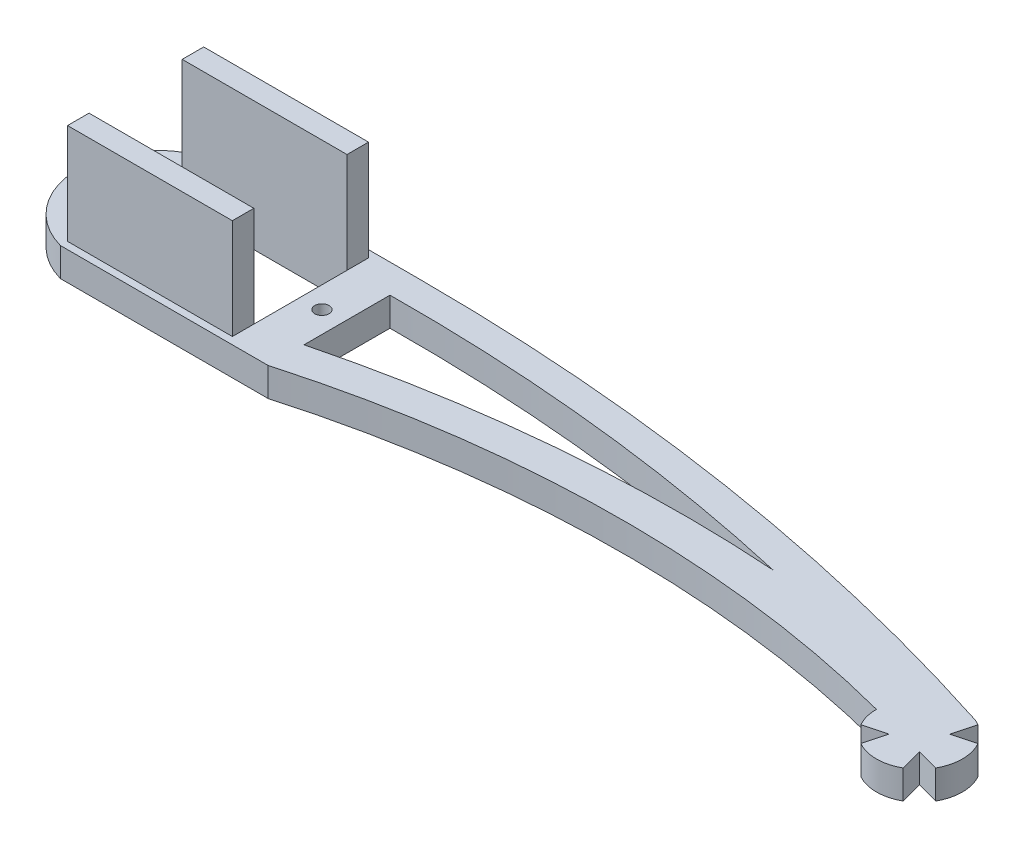
SolidWorks part; units mm, degrees
ref_plane "前视基准面" through (0, 0, 0) normal (0, 0, 1) x (1, 0, 0)
ref_plane "上视基准面" through (0, 0, 0) normal (0, 1, 0) x (1, 0, 0)
ref_plane "右视基准面" through (0, 0, 0) normal (1, 0, 0) x (0, 0, -1)
sketch "草图1" plane through (0, 0, 0) normal (0, 1, 0) x (1, 0, 0)
  line L0 (17.5, -10.5) -> (-11.5, -10.5)
  line L1 (-11.5, -6.5) -> (11.5, -6.5)
  line L2 (-11.5, -6.5) -> (-11.5, 6.5)
  line L3 (-11.5, 6.5) -> (11.5, 6.5)
  line L4 (11.5, -6.5) -> (11.5, 6.5)
  line L5 (-11.5, -6.5) -> (11.5, 6.5) construction
  line L6 (-11.5, 6.5) -> (11.5, -6.5) construction
  line L7 (-11.5, 3) -> (-12.5, 3)
  line L9 (-11.5, -3) -> (-12.5, -3)
  line L10 (-12.5, 3) -> (-12.5, -3)
  line L11 (0, 0) -> (50000, 0) construction
  line L12 (17.5, 10.5) -> (-11.5, 10.5)
  line L13 (17.5, -10.5) -> (17.5, 10.5)
  arc A1 (-11.5, -10.5) -> (-11.5, 10.5) centre (-8.6094, 0) cw
  point P0 (0, 0)
  point P14 (-12.5, 0)
  point P20 (-19.5, 0)
  dimension "D5" = 4
  dimension "D6" = 8
  dimension "D1" = 23
  dimension "D2" = 13
  dimension "D3" = 1
  dimension "D4" = 6
  dimension "D7" = 6
extrude "凸台-拉伸1" add sketch "草图1" along normal mid plane 4 contours A1 L0 L13 L12 L10 L7 L2 L3 L4 L1 L9
sketch "草图2" plane through (0, 2, 0) normal (0, 1, 0) x (1, 0, 0)
  line L0 (17.5, 10.5) -> (-11.5, 10.5) construction
  line L1 (11.5, -6.5) -> (11.5, 6.5) construction
  line L2 (107.5, -9.6143) -> (98.1207, -9.6143) construction
  line L3 (17.5, -10.5) -> (17.5, 10.5)
  line L4 (17.5, -5.5) -> (17.5, 6.5)
  line L5 (-11.5, -6.5) -> (11.5, -6.5) construction
  line L7 (-11.5, 6.5) -> (11.5, 6.5) construction
  arc A0 (17.5, -10.5) -> (101.5, -9.6143) centre (61.1278, -164.4371) cw
  arc A1 (17.5, 10.5) -> (109.3367, -3.9024) centre (17.5, -289.5) cw
  circle A2 centre (107.5, -9.6143) radius 6
  arc A3 (17.5, 6.5) -> (77.5, 0) centre (19.6864, -253.4908) cw
  arc A4 (17.5, -5.5) -> (77.5, 0) centre (64.6245, -189.5632) cw
  point P16 (64.5211, -2.4548)
  point P21 (0, 0)
  point P22 (63.9796, 0)
  point P23 (62.1867, 2.2524)
  point P24 (81.2486, -1.2004)
  point P27 (77.5, 0)
  point P28 (77.5, 0.3514)
  point P29 (0, 0)
  point P31 (17.5, 6.2378)
  point P32 (0, 0)
  dimension "D1" = 160
  dimension "D2" = 300
  dimension "D3" = 12
  dimension "D5" = 260
  dimension "D6" = 190
  dimension "D4" = 90
  dimension "D7" = 6
  dimension "D8" = 1
  dimension "D9" = 60
extrude "凸台-拉伸2" add sketch "草图2" against normal blind 4
sketch "草图4" plane through (0, -2, 0) normal (0, -1, 0) x (1, 0, 0)
  line L0 (107.5, 9.6143) -> (88.0492, 9.6143) construction
  line L1 (107.5, 9.6143) -> (100.5212, 16.5931) construction
  line L2 (105.3787, 11.7356) -> (104.5475, 14.8376)
  line L3 (105.3787, 11.7356) -> (102.2767, 12.5668)
  line L4 (109.6213, 11.7356) -> (112.7233, 12.5668)
  line L5 (109.6213, 11.7356) -> (110.4525, 14.8376)
  line L6 (109.6213, 7.493) -> (110.4525, 4.391)
  line L7 (109.6213, 7.493) -> (112.7233, 6.6618)
  line L10 (105.3787, 7.493) -> (104.5475, 4.391) [skipped]
  line L11 (105.3787, 7.493) -> (102.2767, 6.6618) [skipped]
  line L12 (-11.5, -10.5) -> (17.5, -10.5)
  line L13 (17.5, 10.5) -> (-11.5, 10.5)
  line L14 (-11.5, -10.5) -> (17.5, -10.5)
  line L15 (17.5, 10.5) -> (-11.5, 10.5)
  circle A0 centre (107.5, 9.6143) radius 3
  arc A1 (109.3367, 3.9024) -> (101.5, 9.6143) centre (107.5, 9.6143) ccw construction
  circle A2 centre (107.5, 9.6143) radius 3
  circle A3 centre (107.5, 9.6143) radius 3
  circle A4 centre (107.5, 9.6143) radius 3
  arc A9 (17.5, -10.5) -> (109.3367, 3.9024) centre (17.5, 289.5) ccw
  arc A10 (109.3367, 3.9024) -> (101.5, 9.6143) centre (107.5, 9.6143) ccw
  arc A11 (17.5, 10.5) -> (101.5, 9.6143) centre (61.1278, 164.4371) ccw
  arc A12 (-11.5, 10.5) -> (-11.5, -10.5) centre (-8.6094, 0) ccw
  arc A13 (17.5, -10.5) -> (109.3367, 3.9024) centre (17.5, 289.5) ccw
  arc A14 (109.3367, 3.9024) -> (101.5, 9.6143) centre (107.5, 9.6143) ccw
  arc A15 (17.5, 10.5) -> (101.5, 9.6143) centre (61.1278, 164.4371) ccw
  arc A16 (-11.5, 10.5) -> (-11.5, -10.5) centre (-8.6094, 0) ccw
  arc M5 (109.3367, 3.9024) -> (101.5, 9.6143) centre (107.5, 9.6143) ccw
  dimension "D2" = 6
  dimension "D1" = 45
  dimension "D3" = 60
  dimension "D5" = 0
  dimension "D4" = 4
extrude "切除-拉伸1" cut sketch "草图4" against normal through all both and the other way through all contours L3 L2 M5 | L5 L4 M5 | L7 L6 M5
sketch "草图5" plane through (0, -2, 0) normal (0, -1, 0) x (1, 0, 0)
  line L0 (11.5, 6.5) -> (11.5, -6.5) construction
  line L1 (-11.5, -3) -> (-11.5, -6.5) construction
  circle A0 centre (14.5, 0) radius 1
  circle A1 centre (-14.5, 0) radius 1
  point P9 (-11.5, -4.75)
  dimension "D1" = 3
  dimension "D2" = 2
  dimension "D3" = 2
  dimension "D4" = 3
extrude "切除-拉伸2" cut sketch "草图5" against normal through all both and the other way through all
sketch "草图6" plane through (0, 2, 0) normal (0, 1, 0) x (1, 0, 0)
  line L0 (11.5, -6.5) -> (11.5, 6.5) construction
  line L1 (-11.5, -6.5) -> (11.5, -6.5)
  line L2 (-11.5, -6.5) -> (-11.5, -9.5)
  line L3 (-11.5, -9.5) -> (11.5, -9.5)
  line L4 (11.5, -6.5) -> (11.5, -9.5)
  dimension "D1" = 3
extrude "凸台-拉伸3" add sketch "草图6" along normal blind 14
mirror "镜向1" about plane through (0, 0, 0) normal (0, 0, 1) of "凸台-拉伸3"
